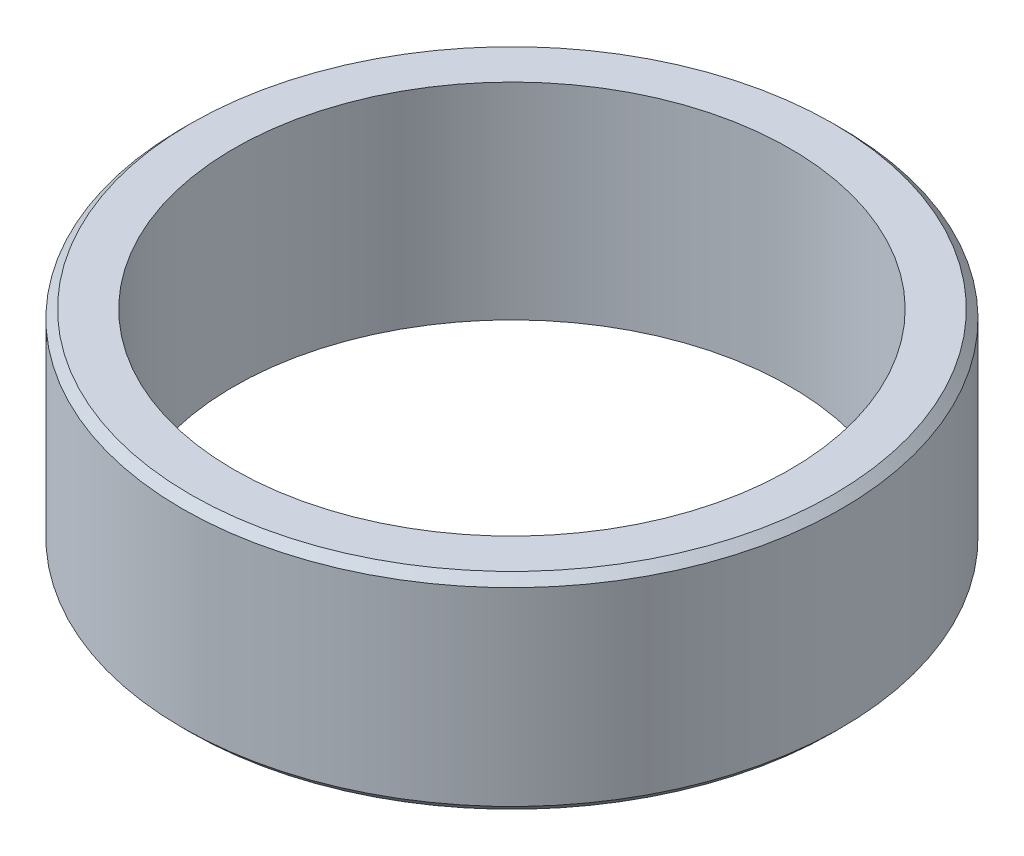
SolidWorks part; units mm, degrees
ref_plane "Front Plane" through (0, 0, 0) normal (0, 0, 1) x (1, 0, 0)
ref_plane "Top Plane" through (0, 0, 0) normal (0, 1, 0) x (1, 0, 0)
ref_plane "Right Plane" through (0, 0, 0) normal (1, 0, 0) x (0, 0, -1)
sketch "Sketch1" plane through (0, 0, 0) normal (0, 1, 0) x (1, 0, 0)
  circle A0 centre (0, 0) radius 6.75
  circle A1 centre (0, 0) radius 8
  dimension "D1" = 13.5
  dimension "D2" = 16
extrude "Boss-Extrude1" add sketch "Sketch1" along normal blind 5
chamfer "Chamfer1" distance 0.2 angle 45 2 edges at (0, 0, 8) (0, 5, 8)
